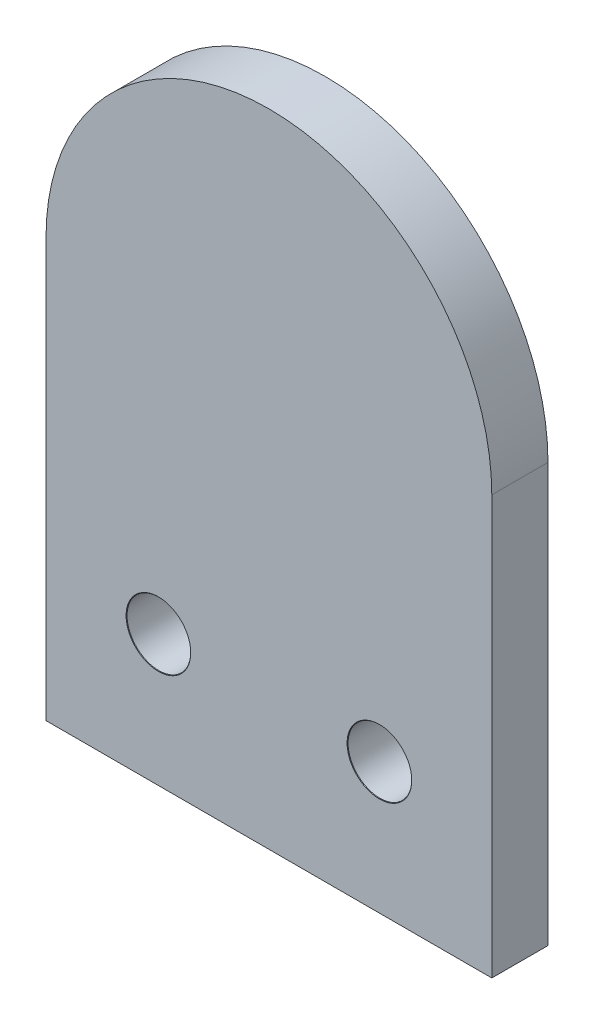
SolidWorks part; units mm, degrees
ref_plane "Front Plane" through (0, 0, 0) normal (0, 0, 1) x (1, 0, 0)
ref_plane "Top Plane" through (0, 0, 0) normal (0, 1, 0) x (1, 0, 0)
ref_plane "Right Plane" through (0, 0, 0) normal (1, 0, 0) x (0, 0, -1)
sketch "Sketch1" plane through (0, 0, 0) normal (0, 0, 1) x (1, 0, 0)
  line L0 (-11.9, 0) -> (-11.9, -22.34)
  line L1 (-11.9, -22.34) -> (11.9, -22.34)
  line L2 (11.9, -22.34) -> (11.9, 0)
  arc A0 (11.9, 0) -> (-11.9, 0) centre (0, 0) ccw
  dimension "D1" = 22.34
  dimension "D2" = 23.8
extrude "Boss-Extrude1" add sketch "Sketch1" along normal blind 3
sketch "Sketch2" plane through (0, 0, 0) normal (0, 0, -1) x (-1, 0, 0)
  circle A0 centre (0, 0) radius 6 construction
  circle A1 centre (0, 6) radius 1.95
  circle A2 centre (6, 0) radius 1.95
  circle A3 centre (0, -6) radius 1.95
  circle A4 centre (-6, 0) radius 1.95
  point P14 (0, 0)
  dimension "D1" = 12
  dimension "D2" = 3.9
  dimension "D3" = 4
extrude "Boss-Extrude2" add sketch "Sketch2" along normal blind 3
hole_wizard "M3 Clearance Hole1" positions "3DSketch1" profile "Sketch5" hole size "M3" standard "ANSI Metric" end condition through all
sketch3d "3DSketch1"
  line L0 (-11.9, -22.34, 3) -> (11.9, -22.34, 3) construction
  line L1 (-11.9, 0, 3) -> (-11.9, -22.34, 3) construction
  line L2 (11.9, -22.34, 3) -> (11.9, 0, 3) construction
  point P0 (-5.9, -15.34, 3)
  point P2 (5.9, -15.34, 3)
  dimension "D1" = 7
  dimension "D2" = 6
  dimension "D3" = 6
sketch "Sketch5" plane through (-5.9, -15.34, 3) normal (1, 0, 0) x (0, -1, 0)
  line L0 (0, 0) -> (0, 6)
  line L1 (0, 6) -> (1.7, 6)
  line L2 (1.7, 6) -> (1.7, 0.025)
  line L3 (1.7, 0.025) -> (1.725, 0)
  line L5 (1.725, 0) -> (0, 0)
  line L6 (-1.7, 0.025) -> (-1.725, 0) construction
  line L11 (0, -6.35) -> (0, 107.95) construction
  dimension "Thru Hole Dia." = 3.4
  dimension "Thru Hole Depth" = 6
  dimension "Near C'Sink Dia." = 3.45
  dimension "Near C'Sink Angle" = 90
